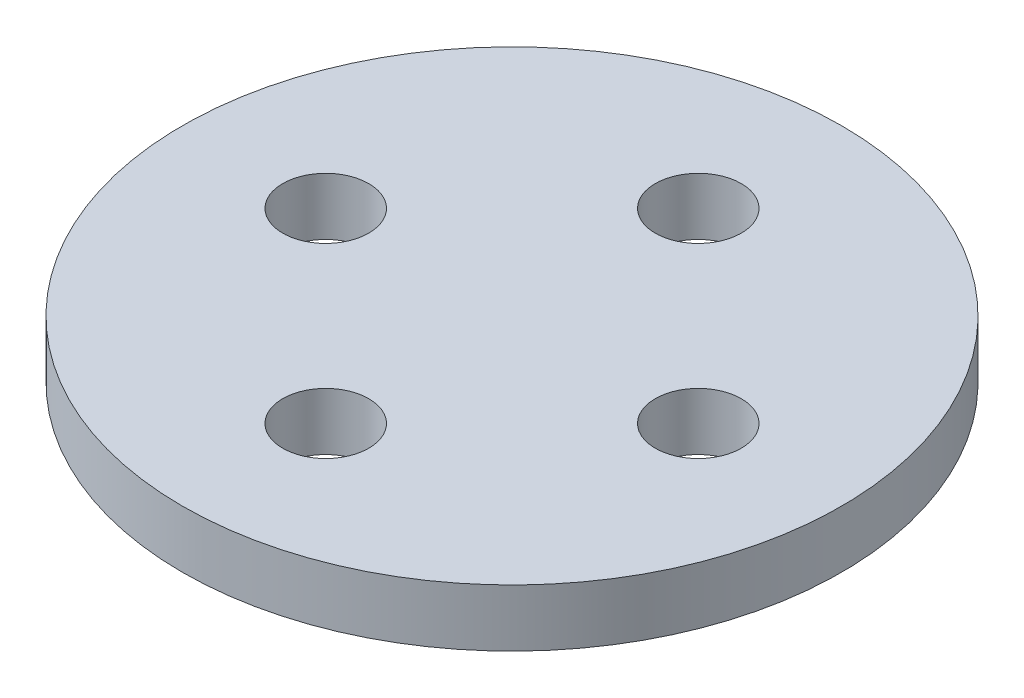
SolidWorks part; units mm, degrees
ref_plane "Front Plane" through (0, 0, 0) normal (0, 0, 1) x (1, 0, 0)
ref_plane "Top Plane" through (0, 0, 0) normal (0, 1, 0) x (1, 0, 0)
ref_plane "Right Plane" through (0, 0, 0) normal (1, 0, 0) x (0, 0, -1)
sketch "Sketch1" plane through (0, 0, 0) normal (0, 1, 0) x (1, 0, 0)
  circle A0 centre (0, 0) radius 11.5
  dimension "D1" = 23
extrude "Boss-Extrude1" add sketch "Sketch1" along normal blind 2
sketch "Sketch2" plane through (0, 0, 0) normal (0, -1, 0) x (1, 0, 0)
  circle A0 centre (6.5, 0) radius 1.5 construction
  circle A1 centre (0, -6.5) radius 1.5 construction
  circle A2 centre (-6.5, 0) radius 1.5 construction
  circle A3 centre (0, 6.5) radius 1.5 construction
  circle A4 centre (6.5, 0) radius 1.5
  circle A5 centre (0, -6.5) radius 1.5
  circle A6 centre (-6.5, 0) radius 1.5
  circle A7 centre (0, 6.5) radius 1.5
extrude "Cut-Extrude1" cut sketch "Sketch2" against normal through all
